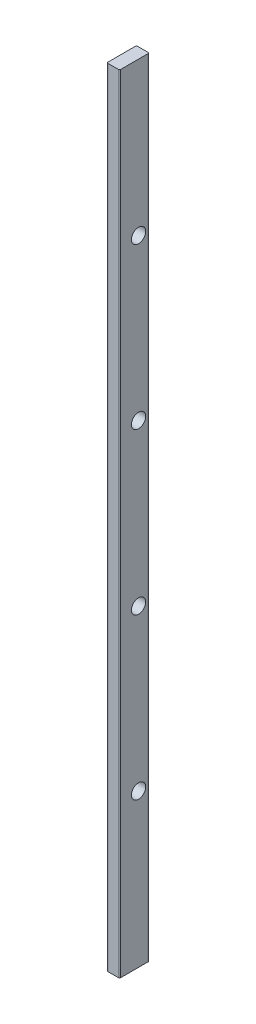
SolidWorks part; units mm, degrees
ref_plane "Front" through (0, 0, 0) normal (0, 0, 1) x (1, 0, 0)
ref_plane "Top" through (0, 0, 0) normal (0, 1, 0) x (1, 0, 0)
ref_plane "Right" through (0, 0, 0) normal (1, 0, 0) x (0, 0, -1)
sketch "Sketch1" plane through (0, 0, 0) normal (0, 1, 0) x (1, 0, 0)
  line L1 (-19.05, -44.45) -> (19.05, -44.45)
  line L2 (-19.05, -44.45) -> (-19.05, 44.45)
  line L3 (-19.05, 44.45) -> (19.05, 44.45)
  line L5 (-19.05, -44.45) -> (19.05, 44.45) construction
  line L6 (-19.05, 44.45) -> (19.05, -44.45) construction
  line L7 (19.05, 34.3752) -> (19.05, 44.45) construction
  line L8 (19.05, -44.45) -> (19.05, 44.45)
  line L9 (17.4625, 44.45) -> (19.05, 44.45) construction
  point P0 (0, 0)
  dimension "D1" = 38.1
  dimension "D2" = 88.9
extrude "Boss-Extrude1" add sketch "Sketch1" along normal blind 2362.2
sketch "Sketch2" plane through (-19.05, 0, 0) normal (1, 0, 0) x (0, 0, -1)
  line L0 (44.45, 0) -> (-44.45, 0) construction
  line L1 (44.45, 2362.2) -> (44.45, 0) construction
  circle A0 centre (12.7, 458.7875) radius 21.4313
  circle A1 centre (12.7, 939.8) radius 21.4313
  dimension "D1" = 42.8625
  dimension "D2" = 31.75
  dimension "D4" = 481.0125
  dimension "D3" = 458.7875
extrude "Cut-Extrude4" cut sketch "Sketch2" along normal through all
fillet "Fillet1" radius 3.175 4 edges at (19.05, 1181.1, 44.45) (-19.05, 1181.1, 44.45) (-19.05, 1181.1, -44.45) (19.05, 1181.1, -44.45)
ref_plane "Plane1" through (0, 1181.1, 0) normal (0, -1, 0) x (-1, 0, 0)
mirror "Mirror1" about plane through (0, 1181.1, 0) normal (0, -1, 0) of "Cut-Extrude4"
